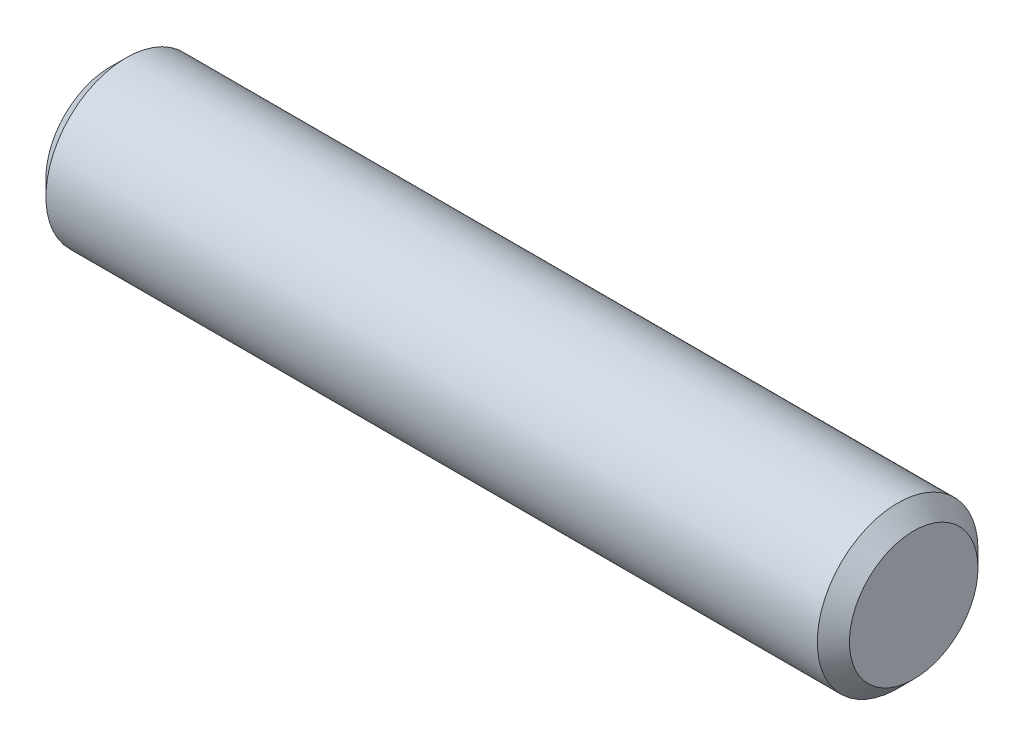
SolidWorks part; units mm, degrees
ref_plane "Front" through (0, 0, 0) normal (0, 0, 1) x (1, 0, 0)
ref_plane "Top" through (0, 0, 0) normal (0, 1, 0) x (1, 0, 0)
ref_plane "Right" through (0, 0, 0) normal (1, 0, 0) x (0, 0, -1)
sketch "Sketch1" plane through (0, 0, 0) normal (0, 0, 1) x (1, 0, 0)
  line L0 (-63.5, 0) -> (63.5, 0) construction
  line L1 (63.5, 12.7) -> (63.5, -12.7) construction
  line L2 (-63.5, 12.7) -> (-63.5, -12.7) construction
  dimension "Length" = 127
  dimension "Diameter" = 25.4
sketch "Sketch2" plane through (0, 0, 0) normal (1, 0, 0) x (0, 0, -1)
  circle A0 centre (0, 0) radius 12.7
extrude "Extrude1" add sketch "Sketch2" against normal up to vertex (63.5 mm away) and the other way up to vertex (63.5 mm away) up to point (-63.5, 12.7, 0) other way up to point (63.5, 12.7, 0)
chamfer "Chamfer1" distance 2.54 angle 45 2 edges at (63.5, 0, -12.7) (-63.5, 0, -12.7)
equation "\"D1@Chamfer1\" = \"Diameter@Sketch1\"*.1"
